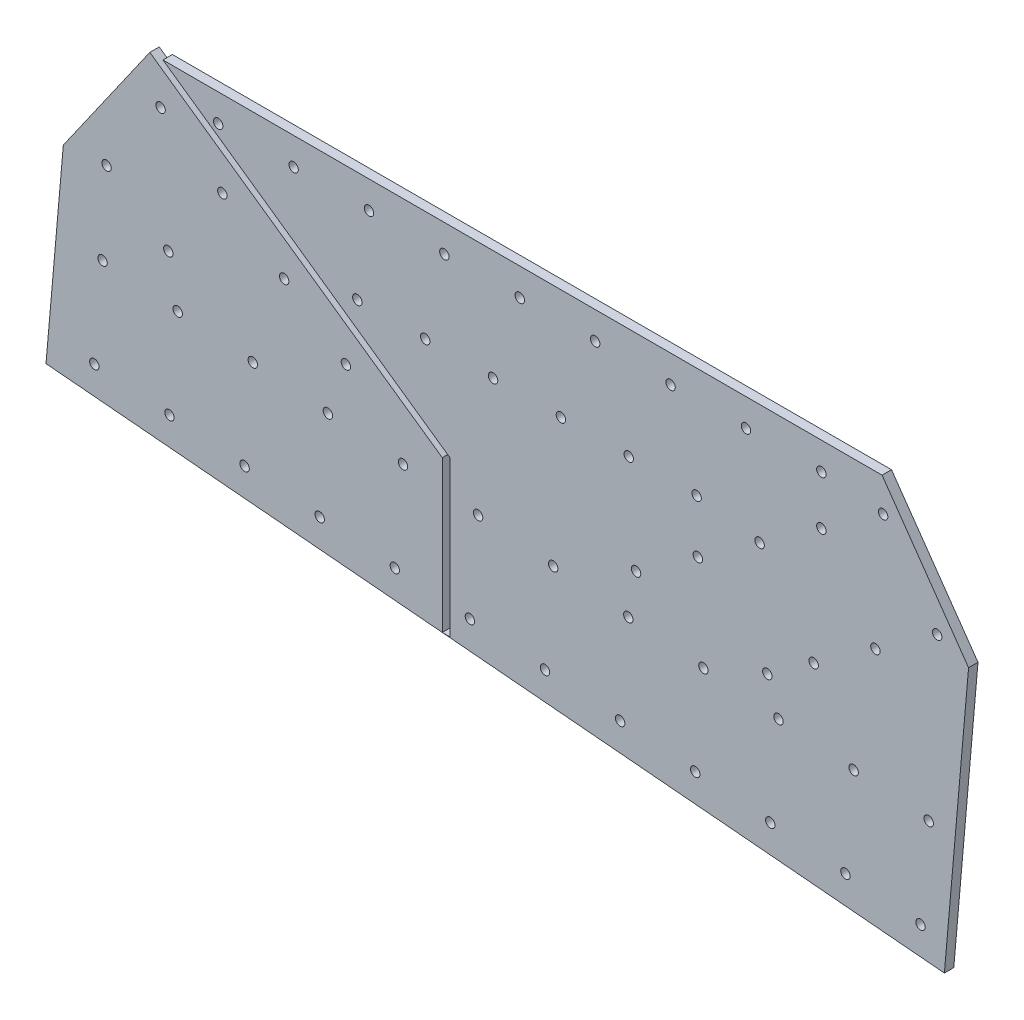
SolidWorks part; units mm, degrees
ref_plane "Front Plane" through (0, 0, 0) normal (0, 0, 1) x (1, 0, 0)
ref_plane "Top Plane" through (0, 0, 0) normal (0, 1, 0) x (1, 0, 0)
ref_plane "Right Plane" through (0, 0, 0) normal (1, 0, 0) x (0, 0, -1)
sketch "Sketch1" plane through (0, 0, 0) normal (0, 0, 1) x (1, 0, 0)
  line L0 (-79.8501, 25.4) -> (-50.7124, -16.2129)
  line L1 (-105.1599, -54.3375) -> (386.2158, 289.7275) construction
  line L2 (-50.7124, -16.2129) -> (-58.8636, -109.3819)
  line L3 (-569.8915, -64.6728) -> (50.1681, -118.9209) construction
  line L4 (-79.8501, 25.4) -> (-326.5499, 25.4)
  line L5 (-326.5499, 25.4) -> (-355.6876, -16.2129)
  line L6 (-329.2379, -34.7332) -> (-762.7793, 268.8357) construction
  line L7 (-355.6876, -16.2129) -> (-361.5222, -82.9027)
  line L8 (-361.5222, -82.9027) -> (-58.8636, -109.3819)
extrude "Boss-Extrude1" add sketch "Sketch1" along normal blind 3.175
sketch "Sketch2" plane through (0, 0, 3.175) normal (0, 0, 1) x (1, 0, 0)
  line L0 (-696.0914, -5.8248) -> (54.3189, -71.4772) construction
  line L1 (-368.2415, -34.5079) -> (-32.3637, -63.8934) construction
  line L2 (-578.3049, -60.7496) -> (50.4448, -115.758) construction
  line L3 (-373.7248, -78.648) -> (-32.3801, -108.5118) construction
  line L4 (-110.0805, -53.907) -> (384.3947, 292.3283) construction
  line L5 (-114.1267, -56.7401) -> (-32.6037, 0.3429) construction
  line L6 (-178.9693, -47.88) -> (358.8992, 328.7396) construction
  line L7 (-183.0154, -50.7131) -> (-64.6346, 32.178) construction
  line L8 (-258.5344, -22.225) -> (-147.8656, -22.225) construction
  line L9 (-264.0698, -22.225) -> (-142.3302, -22.225) construction
  line L10 (-322.0155, 22.225) -> (-84.3845, 22.225) construction
  line L11 (-327.551, 22.225) -> (-78.849, 22.225) construction
  line L12 (-234.3504, -43.0348) -> (-739.9674, 311.0021) construction
  line L13 (-229.1488, -46.677) -> (-334.6907, 27.2243) construction
  line L14 (-322.9121, -35.2866) -> (-765.4629, 274.5908) construction
  line L15 (-317.7105, -38.9288) -> (-362.0313, -7.8951) construction
  line L16 (-61.2906, -11.8212) -> (-82.097, -26.3901) construction
  line L17 (-82.097, -26.3901) -> (-102.9035, -40.9589) construction
  line L18 (-102.9035, -40.9589) -> (-118.5084, -51.8855) construction
  line L19 (-61.2906, -11.8212) -> (-79.5016, 14.1868) construction
  line L20 (-79.5016, 14.1868) -> (-100.3081, -0.382) construction
  line L21 (-100.3081, -0.382) -> (-121.1146, -14.9508) construction
  line L22 (-121.1146, -14.9508) -> (-141.921, -29.5197) construction
  line L23 (-141.921, -29.5197) -> (-162.7275, -44.0885) construction
  line L24 (-322.9077, 11.1148) -> (-302.1012, -3.454) construction
  line L25 (-302.1012, -3.454) -> (-281.2948, -18.0228) construction
  line L26 (-281.2948, -18.0228) -> (-260.4883, -32.5917) construction
  line L27 (-322.9077, 11.1148) -> (-341.1188, -14.8932) construction
  line L28 (-341.1188, -14.8932) -> (-320.3123, -29.4621) construction
  circle A0 centre (-66.8952, -99.241) radius 1.5875
  circle A1 centre (-92.1986, -97.0272) radius 1.5875
  circle A2 centre (-117.5019, -94.8134) radius 1.5875
  circle A3 centre (-142.8053, -92.5997) radius 1.5875
  circle A4 centre (-168.1086, -90.3859) radius 1.5875
  circle A5 centre (-193.412, -88.1722) radius 1.5875
  circle A6 centre (-218.7153, -85.9584) radius 1.5875
  circle A7 centre (-244.0187, -83.7447) radius 1.5875
  circle A8 centre (-269.322, -81.5309) radius 1.5875
  circle A9 centre (-294.6253, -79.3172) radius 1.5875
  circle A10 centre (-319.9287, -77.1034) radius 1.5875
  circle A11 centre (-345.232, -74.8896) radius 1.5875
  circle A12 centre (-89.4314, -65.398) radius 1.5875
  circle A13 centre (-114.7347, -63.1843) radius 1.5875
  circle A14 centre (-140.0381, -60.9705) radius 1.5875
  circle A15 centre (-165.3414, -58.7568) radius 1.5875
  circle A16 centre (-190.6448, -56.543) radius 1.5875
  circle A17 centre (-215.9481, -54.3292) radius 1.5875
  circle A18 centre (-241.2515, -52.1155) radius 1.5875
  circle A19 centre (-266.5548, -49.9017) radius 1.5875
  circle A20 centre (-291.8582, -47.688) radius 1.5875
  circle A21 centre (-317.1615, -45.4742) radius 1.5875
  circle A22 centre (-342.4648, -43.2605) radius 1.5875
  circle A23 centre (-64.128, -67.6118) radius 1.5875
  circle A24 centre (-61.2906, -11.8212) radius 1.5875
  circle A25 centre (-82.097, -26.3901) radius 1.5875
  circle A26 centre (-102.9035, -40.9589) radius 1.5875
  circle A27 centre (-118.5084, -51.8855) radius 1.5875
  circle A28 centre (-162.7275, -44.0885) radius 1.5875
  circle A29 centre (-141.921, -29.5197) radius 1.5875
  circle A30 centre (-121.1146, -14.9508) radius 1.5875
  circle A31 centre (-100.3081, -0.382) radius 1.5875
  circle A32 centre (-79.5016, 14.1868) radius 1.5875
  circle A33 centre (-100.3081, 16.1398) radius 1.5875
  circle A34 centre (-125.7081, 16.1398) radius 1.5875
  circle A35 centre (-151.1081, 16.1398) radius 1.5875
  circle A36 centre (-176.5081, 16.1398) radius 1.5875
  circle A37 centre (-201.9081, 16.1398) radius 1.5875
  circle A38 centre (-227.3081, 16.1398) radius 1.5875
  circle A39 centre (-252.7081, 16.1398) radius 1.5875
  circle A40 centre (-278.1081, 16.1398) radius 1.5875
  circle A41 centre (-303.5081, 16.1398) radius 1.5875
  circle A42 centre (-142.3302, -11.8212) radius 1.5875
  circle A43 centre (-165.1902, -11.8212) radius 1.5875
  circle A44 centre (-188.0502, -11.8212) radius 1.5875
  circle A45 centre (-210.9102, -11.8212) radius 1.5875
  circle A46 centre (-233.7702, -11.8212) radius 1.5875
  circle A47 centre (-256.6302, -11.8212) radius 1.5875
  circle A48 centre (-322.9077, 11.1148) radius 1.5875
  circle A49 centre (-341.1188, -14.8932) radius 1.5875
  circle A52 centre (-302.1012, -3.454) radius 1.5875
  circle A53 centre (-281.2948, -18.0228) radius 1.5875
  circle A54 centre (-260.4883, -32.5917) radius 1.5875
  circle A55 centre (-320.3123, -29.4621) radius 1.5875
  dimension "D1" = 12
  dimension "D3" = 25.4
  dimension "D5" = 19.05
  dimension "D11" = 3.175
  dimension "D12" = 3.175
  dimension "D14" = 3.175
  dimension "D16" = 3.175
  dimension "D22" = 3.175
  dimension "D4" = 25.4
  dimension "D6" = 31.75
  dimension "D7" = 25.4
  dimension "D8" = 25.4
  dimension "D9" = 25.4
  dimension "D10" = 25.4
  dimension "D13" = 9
  dimension "D15" = 6
  dimension "D17" = 25.4
  dimension "D18" = 25.4
  dimension "D19" = 25.4
  dimension "D20" = 31.75
  dimension "D21" = 25.4
  dimension "D2" = 2
extrude "Cut-Extrude1" cut sketch "Sketch2" against normal up to next (3.175 mm away)
sketch "Sketch3" plane through (0, 0, 0) normal (0, 0, -1) x (-1, 0, 0)
  line L0 (228.0246, -94.5822) -> (228.0246, -43.5882)
  line L1 (228.0246, -43.5882) -> (326.5499, 25.4)
  line L2 (361.5222, -82.9027) -> (58.8636, -109.3819) construction
  line L3 (225.4846, -94.5822) -> (225.4846, -42.266)
  line L4 (225.4846, -42.266) -> (322.1216, 25.4)
  line L5 (228.0246, -94.5822) -> (225.4846, -94.5822)
  line L7 (322.1216, 25.4) -> (326.5499, 25.4)
  line L8 (79.8501, 25.4) -> (326.5499, 25.4) construction
  line L9 (228.0246, -43.5882) -> (733.6416, 310.4487) construction
  line L10 (225.4846, -42.266) -> (732.1847, 312.5293) construction
  dimension "D1" = 2.54
extrude "Cut-Extrude2" cut sketch "Sketch3" against normal up to next
